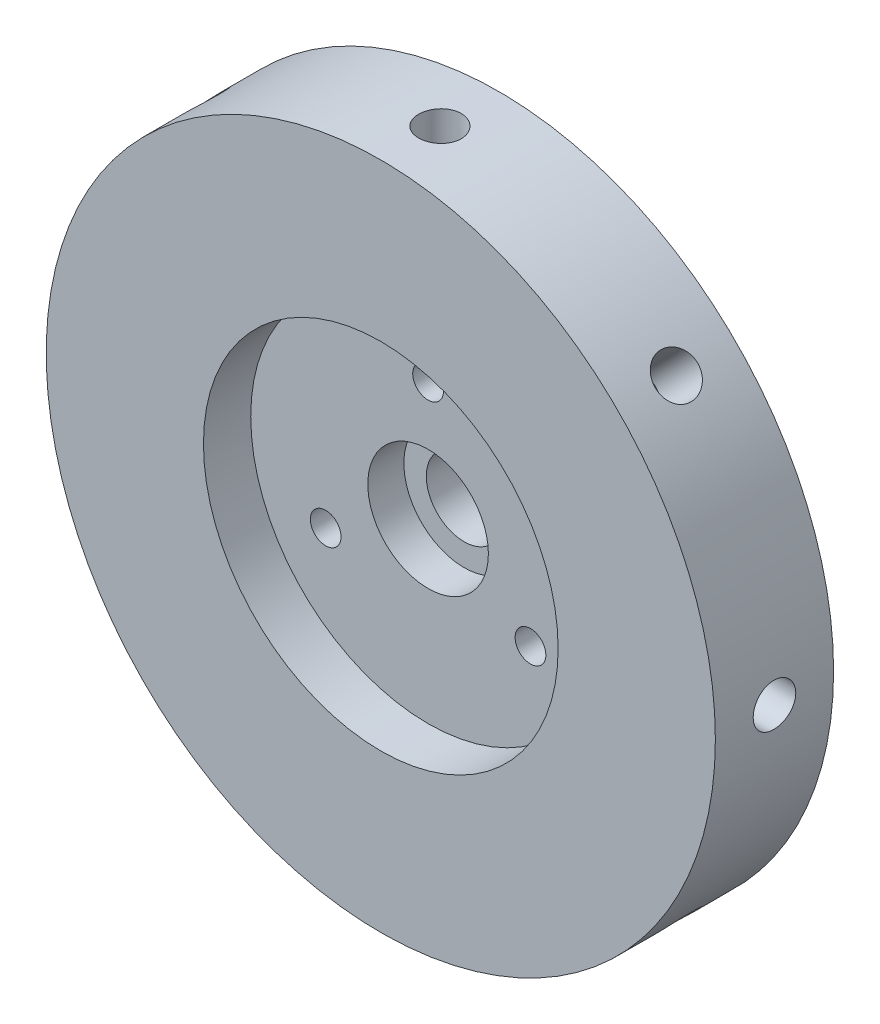
SolidWorks part; units mm, degrees
ref_plane "정면" through (0, 0, 0) normal (0, 0, 1) x (1, 0, 0)
ref_plane "윗면" through (0, 0, 0) normal (0, 1, 0) x (1, 0, 0)
ref_plane "우측면" through (0, 0, 0) normal (1, 0, 0) x (0, 0, -1)
sketch "스케치1" plane through (0, 0, 0) normal (0, 0, 1) x (1, 0, 0)
  circle A0 centre (0, 0) radius 20
  dimension "D1" = 40
extrude "보스-돌출1" add sketch "스케치1" along normal blind 0.0001
sketch "스케치2" plane through (0, 0, 0) normal (0, 0, -1) x (-1, 0, 0)
  line L0 (0, 14.33) -> (0, 0) construction
  line L1 (0, 14.33) -> (12.4101, -7.165) construction
  line L2 (12.4101, -7.165) -> (-12.4101, -7.165) construction
  line L3 (-12.4101, -7.165) -> (0, 14.33) construction
  circle A0 centre (0, 0) radius 14.33 construction
  circle A1 centre (0, 14.33) radius 4.35
  circle A2 centre (-12.4101, -7.165) radius 4.35
  circle A3 centre (12.4101, -7.165) radius 4.35
  dimension "D1" = 28.66
  dimension "D2" = 14.33
  dimension "D4" = 8.7
  dimension "D5" = 8.7
  dimension "D6" = 8.7
  dimension "D3" = 60
extrude "보스-돌출2" add sketch "스케치2" along normal blind 1
sketch "스케치3" plane through (0, 0, -1) normal (0, 0, -1) x (-1, 0, 0)
  circle A0 centre (0, 14.33) radius 3.85
  circle A1 centre (-12.4101, -7.165) radius 3.85
  circle A2 centre (12.4101, -7.165) radius 3.85
  dimension "D1" = 7.7
  dimension "D2" = 7.7
  dimension "D3" = 7.7
extrude "보스-돌출3" add sketch "스케치3" along normal blind 5.5
sketch "스케치4" plane through (0, 0, 0) normal (0, 0, -1) x (-1, 0, 0)
  line L0 (-7.4478, 4.3) -> (0, -8.6) construction
  line L1 (0, -8.6) -> (7.4478, 4.3) construction
  line L2 (7.4478, 4.3) -> (-7.4478, 4.3) construction
  line L3 (0, 0) -> (0, 8.6) construction
  line L4 (-7.4478, 4.3) -> (0, 0) construction
  circle A0 centre (0, 0) radius 8.6 construction
  dimension "D1" = 17.2
  dimension "D2" = 60
  dimension "D3" = 60
sketch "스케치7" plane through (0, 0, 0.0001) normal (0, 0, 1) x (1, 0, 0)
  circle A0 centre (0, 0) radius 28.3
  dimension "D1" = 56.6
extrude "보스-돌출4" add sketch "스케치7" along normal blind 10
ref_plane "평면2" through (0, 28.3, 0) normal (0, 1, 0) x (1, 0, 0)
sketch "스케치8" plane through (0, 28.3, 0) normal (0, 1, 0) x (1, 0, 0)
  line L1 (-28.3, -0.0001) -> (-28.3, -10.0001)
  line L2 (-28.3, -10.0001) -> (28.3, -10.0001)
  line L3 (28.3, -10.0001) -> (28.3, -0.0001)
  line L4 (28.3, -0.0001) -> (-28.3, -0.0001)
  point P0 (0, -5.0001)
  dimension "D1" = 5
  dimension "D2" = 28.3
hole_wizard "M3 여유 구멍5" positions "스케치18" profile "스케치19" hole size "M3" standard "ISO"
sketch "스케치18" plane through (0, 28.3, 0) normal (0, 1, 0) x (1, 0, 0)
  point P0 (0, -5.0001)
sketch "스케치19" plane through (0, 28.3, 5.0001) normal (1, 0, 0) x (0, 0, 1)
  line L0 (0, 0) -> (0, 6.0815)
  line L1 (0, 6.0815) -> (1.8, 5)
  line L2 (1.8, 5) -> (1.8, 0)
  line L5 (1.8, 0) -> (0, 0)
  line L10 (0, 6.0815) -> (-1.8, 5) construction
  line L11 (0, -6.35) -> (0, 107.95) construction
  dimension "구멍 지름" = 3.6
  dimension "구멍 깊이" = 5
  dimension "드릴 각도" = 118
pattern_circular "원형 패턴2" count 8 over 360 about axis through (0, 0, 10.0001) along (0, 0, 1) of "M3 여유 구멍5"
sketch "스케치20" plane through (0, 0, 0) normal (0, 0, -1) x (-1, 0, 0)
  circle A0 centre (0, 0) radius 3.5
  circle A1 centre (0, 0) radius 4
  dimension "D1" = 7
  dimension "D2" = 8
extrude "보스-돌출5" add sketch "스케치20" along normal blind 2
sketch "스케치21" plane through (0, 0, 0) normal (0, 0, -1) x (-1, 0, 0)
  circle A0 centre (0, 0) radius 3.2
  dimension "D1" = 6.4
extrude "컷-돌출1" cut sketch "스케치21" against normal through all
sketch "스케치22" plane through (0, 0, 10.0001) normal (0, 0, 1) x (1, 0, 0)
  circle A0 centre (0, 0) radius 15
  dimension "D1" = 30
extrude "컷-돌출2" cut sketch "스케치22" against normal blind 4
sketch "스케치23" plane through (0, 0, 6.0001) normal (0, 0, 1) x (1, 0, 0)
  circle A0 centre (0, 0) radius 5.1
  dimension "D1" = 10.2
extrude "컷-돌출3" cut sketch "스케치23" against normal blind 3.05
sketch "스케치25" plane through (0, 0, 6.0001) normal (0, 0, 1) x (1, 0, 0)
  line L0 (0, 0) -> (0, 10) construction
  line L1 (0, 0) -> (8.6603, -5) construction
  line L2 (0, 0) -> (-8.6603, -5) construction
  circle A0 centre (0, 0) radius 10 construction
  point P7 (0, 10)
  point P8 (-8.6603, -5)
  point P9 (8.6603, -5)
  dimension "D1" = 20
  dimension "D2" = 120
  dimension "D3" = 120
hole_wizard "M2 여유 구멍1" positions "3D스케치1" profile "스케치26" hole size "M2" standard "ISO"
sketch3d "3D스케치1"
  point P0 (0, 10, 6.0001)
  point P3 (-8.6603, -5, 6.0001)
  point P6 (8.6603, -5, 6.0001)
sketch "스케치26" plane through (0, 10, 6.0001) normal (1, 0, 0) x (0, -1, 0)
  line L0 (0, 0) -> (0, 3.7811)
  line L1 (0, 3.7811) -> (1.3, 3)
  line L2 (1.3, 3) -> (1.3, 0)
  line L5 (1.3, 0) -> (0, 0)
  line L10 (0, 3.7811) -> (-1.3, 3) construction
  line L11 (0, -6.35) -> (0, 107.95) construction
  dimension "구멍 지름" = 2.6
  dimension "구멍 깊이" = 3
  dimension "드릴 각도" = 118
sketch "스케치28" plane through (0, 0, -6.5) normal (0, 0, -1) x (-1, 0, 0)
  circle A0 centre (0, 14.33) radius 2.2
  circle A1 centre (-12.4101, -7.165) radius 2.2
  circle A2 centre (12.4101, -7.165) radius 2.2
  dimension "D1" = 4.4
  dimension "D2" = 4.4
  dimension "D3" = 4.4
extrude "컷-돌출4" cut sketch "스케치28" against normal blind 5.5
